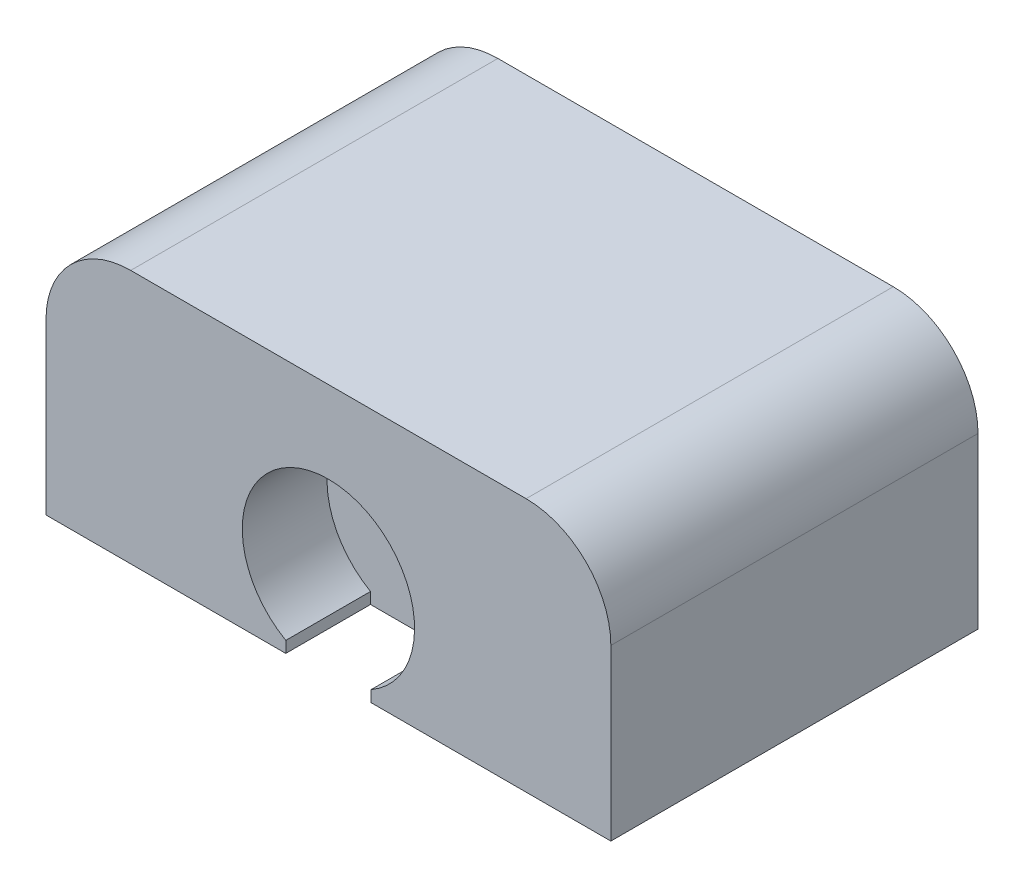
SolidWorks part; units mm, degrees
ref_plane "Front Plane" through (0, 0, 0) normal (0, 0, 1) x (1, 0, 0)
ref_plane "Top Plane" through (0, 0, 0) normal (0, 1, 0) x (1, 0, 0)
ref_plane "Right Plane" through (0, 0, 0) normal (1, 0, 0) x (0, 0, -1)
sketch "Sketch1" plane through (0, 0, 0) normal (0, 0, 1) x (1, 0, 0)
  line L1 (10, 4.5) -> (-10, 4.5)
  line L2 (10, 4.5) -> (10, -4.5)
  line L3 (10, -4.5) -> (-10, -4.5)
  line L4 (-10, 4.5) -> (-10, -4.5)
  line L5 (10, 4.5) -> (-10, -4.5) construction
  line L6 (10, -4.5) -> (-10, 4.5) construction
  point P0 (0, 0)
  dimension "D1" = 20
  dimension "D2" = 9
extrude "Boss-Extrude1" add sketch "Sketch1" along normal blind 13
sketch "Sketch2" plane through (0, 0, 13) normal (0, 0, 1) x (1, 0, 0)
  line L0 (0, -4.5) -> (0, -1.45) construction
  line L1 (-10, -4.5) -> (10, -4.5) construction
  line L2 (1.51, -4.5) -> (-1.51, -4.5)
  line L3 (-1.51, -4.5) -> (-1.51, -4.1)
  line L4 (1.51, -4.5) -> (1.51, -4.1)
  circle A0 centre (0, -1.45) radius 3.05
  point P9 (0, -4.5)
  dimension "D1" = 3.05
  dimension "D2" = 3.02
extrude "Cut-Extrude1" cut sketch "Sketch2" against normal blind 3
fillet "Fillet1" radius 3 2 edges at (-10, 4.5, 6.5) (10, 4.5, 6.5)
